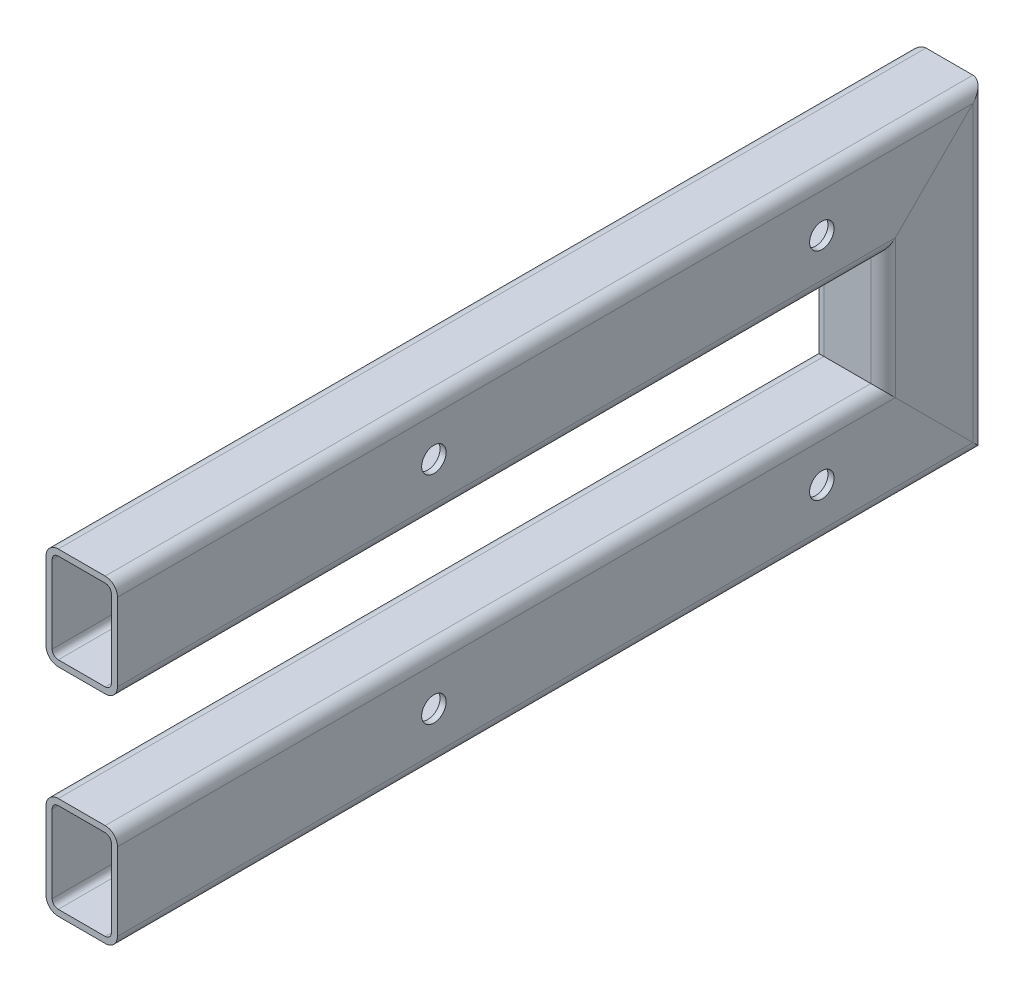
SolidWorks part; units mm, degrees
ref_plane "Front Plane" through (0, 0, 0) normal (0, 0, 1) x (1, 0, 0)
ref_plane "Top Plane" through (0, 0, 0) normal (0, 1, 0) x (1, 0, 0)
ref_plane "Right Plane" through (0, 0, 0) normal (1, 0, 0) x (0, 0, -1)
sketch "Sketch2" plane through (0, 0, 0) normal (1, 0, 0) x (0, 0, -1)
  line L0 (0, 52.92) -> (400, 52.92)
  line L1 (400, 52.92) -> (400, -52.92)
  line L2 (400, -52.92) -> (0, -52.92)
  line L7 (55, 0) -> (-55, 0) construction
  line L8 (0, 55) -> (0, -55) construction
  point P9 (400, 0)
  point P12 (0, 0)
  point P15 (0, 0)
  point P16 (0, 0)
  point P17 (0, 0)
  dimension "D1" = 105.84
  dimension "D2" = 400
sketch "Sketch1" plane through (0, 0, 0) normal (0, 0, 1) x (1, 0, 0)
  line L0 (0, -55) -> (0, 55) construction
  line L1 (6, 77.92) -> (29, 77.92)
  line L2 (0, 71.92) -> (0, 33.92)
  line L3 (6, 27.92) -> (29, 27.92)
  line L4 (35, 71.92) -> (35, 33.92)
  arc A0 (0, 33.92) -> (6, 27.92) centre (6, 33.92) ccw
  arc A1 (29, 27.92) -> (35, 33.92) centre (29, 33.92) ccw
  arc A2 (35, 71.92) -> (29, 77.92) centre (29, 71.92) ccw
  arc A3 (6, 77.92) -> (0, 71.92) centre (6, 71.92) ccw
  point P6 (0, 52.92)
  point P10 (0, 27.92)
  point P15 (35, 77.92)
  point P18 (0, 77.92)
  dimension "D3" = 6
  dimension "D1" = 35
  dimension "D2" = 50
sweep "Sweep-Thin1" add profiles "Sketch1" path "Sketch2" parameters "D1"=3
sketch "Sketch4" plane through (0, 0, 0) normal (1, 0, 0) x (0, 0, -1)
  line L0 (425, 77.92) -> (375, 27.92)
  line L1 (55, 0) -> (-55, 0) construction
  line L2 (425, -77.92) -> (375, -27.92)
  point P8 (0, 0)
  point P9 (0, 0)
  point P10 (0, 0)
  point P12 (0, 0)
  point P14 (0, 0)
split "Split1" trim tools "Sketch4" bodies to split 101 resulting bodies 103 104 105
sketch "Sketch5" plane through (0, 0, 0) normal (1, 0, 0) x (0, 0, -1)
  line L0 (250, 0) -> (155, 52.92) construction
  line L1 (19.25, 0) -> (-19.25, 0) construction
  line L2 (250, 0) -> (250, 108.7452) construction
  line L3 (0, 19.25) -> (0, -19.25) construction
  circle A0 centre (250, 0) radius 108.7452 construction
  circle A1 centre (155, 52.92) radius 6
  circle A2 centre (155, -52.92) radius 6
  circle A3 centre (345, -52.92) radius 6
  circle A4 centre (345, 52.92) radius 6
  point P15 (0, 0)
  dimension "D1" = 105.84
  dimension "D4" = 12
  dimension "D2" = 190
  dimension "D3" = 250
extrude "Cut-Extrude1" cut sketch "Sketch5" along normal through all
